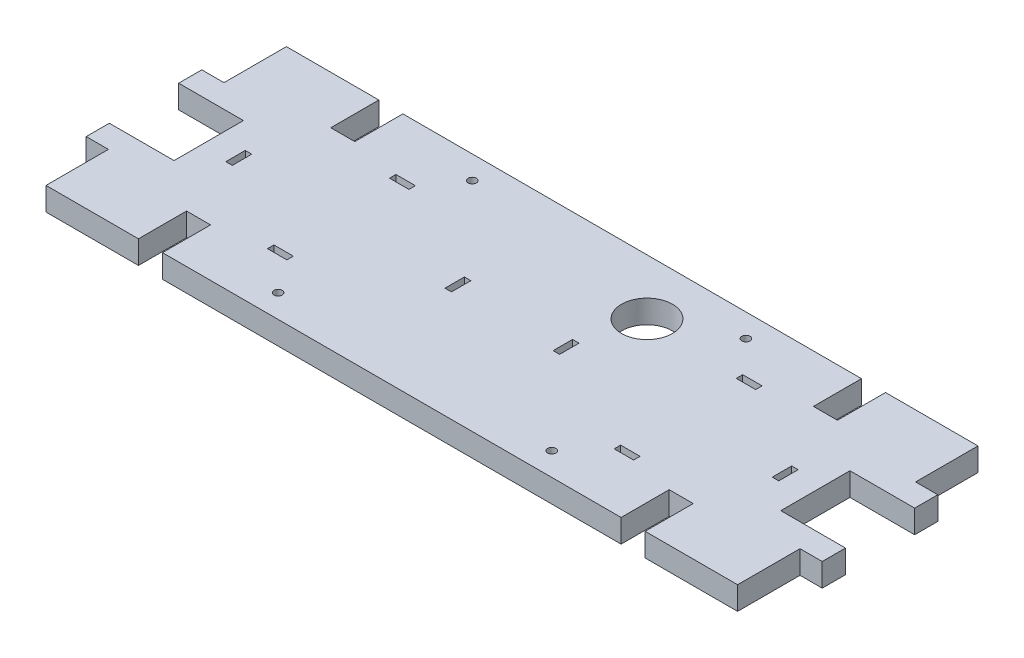
SolidWorks part; units mm, degrees
ref_plane "Front Plane" through (0, 0, 0) normal (0, 0, 1) x (1, 0, 0)
ref_plane "Top Plane" through (0, 0, 0) normal (0, 1, 0) x (1, 0, 0)
ref_plane "Right Plane" through (0, 0, 0) normal (1, 0, 0) x (0, 0, -1)
sketch "Sketch1" plane through (0, 0, 0) normal (0, 1, 0) x (1, 0, 0)
  line L0 (-95.504, 15.875) -> (-101.6, 15.875)
  line L1 (-95.504, 33.02) -> (-70.104, 33.02)
  line L2 (-95.504, 33.02) -> (-95.504, 15.875)
  line L3 (-95.504, -33.02) -> (-70.104, -33.02)
  line L4 (94.488, 33.02) -> (94.488, 15.875)
  line L5 (-101.6, 15.875) -> (-101.6, -15.875)
  line L6 (-101.6, -15.875) -> (-95.504, -15.875)
  line L7 (94.488, 15.875) -> (100.584, 15.875)
  line L8 (100.584, 15.875) -> (100.584, -15.875)
  line L9 (100.584, -15.875) -> (94.488, -15.875)
  line L10 (-63.5, 33.02) -> (2.794, 33.02)
  line L12 (-70.104, 33.02) -> (-70.104, 19.812)
  line L13 (-70.104, 19.812) -> (-63.5, 19.812)
  line L14 (-63.5, 33.02) -> (-63.5, 19.812)
  line L16 (-70.104, -33.02) -> (-70.104, -19.812)
  line L17 (-70.104, -19.812) -> (-63.5, -19.812)
  line L18 (-63.5, -33.02) -> (-63.5, -19.812)
  line L20 (62.484, 33.02) -> (62.484, 19.812)
  line L21 (62.484, 19.812) -> (69.088, 19.812)
  line L22 (69.088, 33.02) -> (69.088, 19.812)
  line L23 (62.484, -19.812) -> (69.088, -19.812)
  line L24 (62.484, -19.812) -> (62.484, -33.02)
  line L26 (69.088, -19.812) -> (69.088, -33.02)
  line L27 (69.088, 33.02) -> (94.488, 33.02)
  line L28 (69.088, -33.02) -> (94.488, -33.02)
  line L29 (94.488, -15.875) -> (94.488, -33.02)
  line L30 (-95.504, -15.875) -> (-95.504, -33.02)
  line L31 (-63.5, -33.02) -> (2.794, -33.02)
  line L38 (9.398, 33.02) -> (62.484, 33.02)
  line L39 (9.398, -33.02) -> (62.484, -33.02)
  line L40 (2.794, 33.02) -> (9.398, 33.02)
  line L41 (2.794, -33.02) -> (9.398, -33.02)
  dimension "D1" = 189.992
  dimension "D2" = 66.04
  dimension "D3" = 31.75
  dimension "D4" = 6.096
  dimension "D5" = 15.875
  dimension "D6" = 33.02
  dimension "D7" = 6.096
  dimension "D8" = 13.208
  dimension "D9" = 13.208
  dimension "D10" = 25.4
  dimension "D11" = 25.4
  dimension "D12" = 6.604
  dimension "D13" = 6.604
  dimension "D14" = 25.4
  dimension "D15" = 6.604
  dimension "D16" = 25.4
  dimension "D17" = 6.604
  dimension "D18" = 13.208
  dimension "D19" = 13.208
  dimension "D23" = 101.6
extrude "Boss-Extrude1" add sketch "Sketch1" along normal blind 6.35
sketch "Sketch2" plane through (0, 6.35, 0) normal (0, 1, 0) x (1, 0, 0)
  line L0 (-0.508, 33.02) -> (-0.508, -33.02) construction
  line L1 (62.484, 33.02) -> (-63.5, 33.02) construction
  line L2 (-63.5, -33.02) -> (62.484, -33.02) construction
  line L3 (-101.6, 0) -> (100.584, 0) construction
  line L4 (-101.6, 15.875) -> (-101.6, -15.875) construction
  line L5 (100.584, -15.875) -> (100.584, 15.875) construction
  line L8 (-50.038, 17.653) -> (-44.704, 17.653)
  line L9 (-50.038, 17.653) -> (-50.038, 15.875)
  line L10 (-50.038, 15.875) -> (-44.704, 15.875)
  line L11 (-44.704, 17.653) -> (-44.704, 15.875)
  line L12 (-50.038, -15.875) -> (-44.704, -15.875)
  line L13 (-50.038, -15.875) -> (-50.038, -17.653)
  line L14 (-50.038, -17.653) -> (-44.704, -17.653)
  line L15 (-44.704, -15.875) -> (-44.704, -17.653)
  line L23 (-50.038, 17.653) -> (-24.638, 17.653) construction
  line L25 (45.212, 17.653) -> (50.546, 17.653)
  line L26 (45.212, 17.653) -> (45.212, 15.875)
  line L27 (45.212, 15.875) -> (50.546, 15.875)
  line L28 (50.546, 17.653) -> (50.546, 15.875)
  line L29 (45.212, -15.875) -> (50.546, -15.875)
  line L30 (45.212, -15.875) -> (45.212, -17.653)
  line L31 (45.212, -17.653) -> (50.546, -17.653)
  line L32 (50.546, -15.875) -> (50.546, -17.653)
  line L40 (45.212, 17.653) -> (70.612, 17.653) construction
  line L42 (-95.504, -15.875) -> (-95.504, -33.02) construction
  circle A1 centre (18.796, 17.78) radius 6.985
  dimension "D2" = 114.3
  dimension "D10" = 13.97
  dimension "D3" = 5.334
  dimension "D4" = 5.334
  dimension "D5" = 1.778
  dimension "D6" = 1.778
  dimension "D7" = 31.75
  dimension "D8" = 15.875
  dimension "D12" = 0
  dimension "D9" = 50.8
  dimension "D13" = 2
extrude "Cut-Extrude1" cut sketch "Sketch2" against normal blind 10.16
sketch "Sketch3" plane through (0, 6.35, 0) normal (0, 1, 0) x (1, 0, 0)
  line L0 (-101.6, 0) -> (100.584, 0) construction
  line L1 (-101.6, 15.875) -> (-101.6, -15.875) construction
  line L2 (100.584, -15.875) -> (100.584, 15.875) construction
  line L4 (-76.454, 2.667) -> (-74.676, 2.667)
  line L5 (-76.454, 2.667) -> (-76.454, -2.667)
  line L6 (-76.454, -2.667) -> (-74.676, -2.667)
  line L7 (-74.676, 2.667) -> (-74.676, -2.667)
  line L8 (-16.256, 2.667) -> (-14.478, 2.667)
  line L9 (-16.256, 2.667) -> (-16.256, -2.667)
  line L10 (-16.256, -2.667) -> (-14.478, -2.667)
  line L11 (-14.478, 2.667) -> (-14.478, -2.667)
  line L12 (13.462, 2.667) -> (15.24, 2.667)
  line L13 (13.462, 2.667) -> (13.462, -2.667)
  line L14 (13.462, -2.667) -> (15.24, -2.667)
  line L16 (73.66, 2.667) -> (75.438, 2.667)
  line L17 (73.66, 2.667) -> (73.66, -2.667)
  line L18 (73.66, -2.667) -> (75.438, -2.667)
  line L19 (75.438, 2.667) -> (75.438, -2.667)
  line L20 (-76.454, 2.667) -> (13.462, 2.667) construction
  line L21 (94.488, -33.02) -> (94.488, -15.875) construction
  line L23 (15.24, 2.667) -> (15.24, -2.667) [skipped]
  line L24 (15.24, 2.667) -> (15.24, -2.667)
  line L26 (-95.504, -15.875) -> (-95.504, -33.02) construction
  dimension "D1" = 5.334
  dimension "D2" = 2.667
  dimension "D3" = 1.778
  dimension "D4" = 5.334
  dimension "D5" = 2.667
  dimension "D6" = 1.778
  dimension "D7" = 58.42
  dimension "D8" = 19.05
  dimension "D10" = 19.05
  dimension "D9" = 2
extrude "Cut-Extrude2" cut sketch "Sketch3" against normal blind 10.16
sketch "Sketch4" plane through (0, 6.35, 0) normal (0, 1, 0) x (1, 0, 0)
  line L0 (-63.5, 33.02) -> (-63.5, 19.812) construction
  line L1 (62.484, 33.02) -> (-63.5, 33.02) construction
  circle A0 centre (-38.1, 26.67) radius 1.1303
  circle A1 centre (37.084, 26.67) radius 1.1303
  circle A2 centre (-38.1, -26.67) radius 1.1303
  circle A3 centre (37.084, -26.67) radius 1.1303
  dimension "D1" = 2.2606
  dimension "D2" = 25.4
  dimension "D3" = 6.35
  dimension "D4" = 2
  dimension "D5" = 2
extrude "Cut-Extrude3" cut sketch "Sketch4" against normal blind 10.16
sketch "Sketch5" plane through (0, 0, 0) normal (0, -1, 0) x (1, 0, 0)
  line L0 (-101.6, -15.875) -> (-101.6, 15.875) construction
  line L1 (-101.6, 9.525) -> (-83.82, 9.525)
  line L2 (-101.6, 9.525) -> (-101.6, -9.525)
  line L3 (-101.6, -9.525) -> (-83.82, -9.525)
  line L4 (-83.82, 9.525) -> (-83.82, -9.525)
  line L5 (-101.6, 15.875) -> (-95.504, 15.875) construction
  line L6 (-95.504, -15.875) -> (-101.6, -15.875) construction
  line L7 (100.584, 15.875) -> (100.584, -15.875) construction
  line L8 (100.584, 9.4742) -> (82.804, 9.4742)
  line L9 (100.584, 9.4742) -> (100.584, -9.525)
  line L10 (100.584, -9.525) -> (82.804, -9.525)
  line L11 (82.804, 9.4742) -> (82.804, -9.525)
  line L12 (94.488, 15.875) -> (100.584, 15.875) construction
  line L13 (100.584, -15.875) -> (94.488, -15.875) construction
  dimension "D1" = 17.78
  dimension "D2" = 6.35
  dimension "D3" = 6.35
  dimension "D4" = 17.78
  dimension "D5" = 6.4008
  dimension "D6" = 6.35
extrude "Cut-Extrude4" cut sketch "Sketch5" against normal blind 10.16
